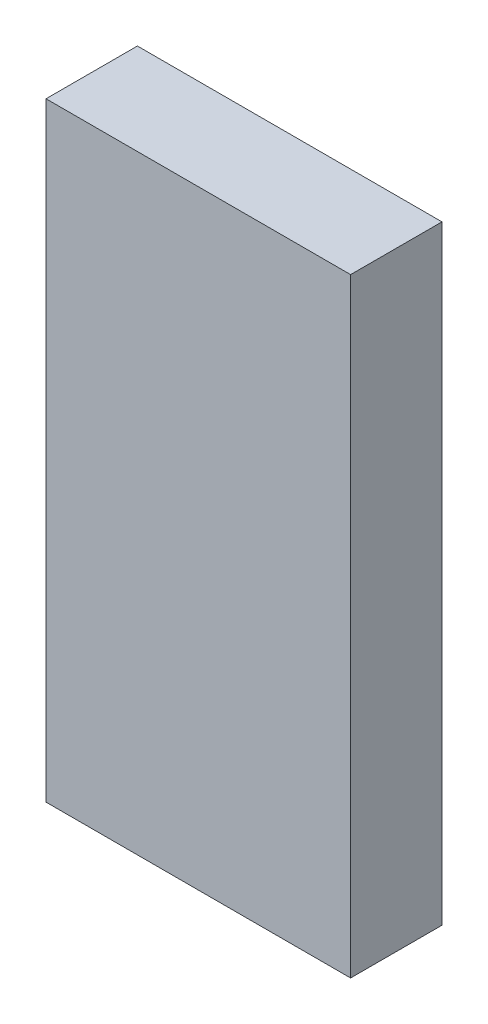
SolidWorks part; units mm, degrees
ref_plane "Front Plane" through (0, 0, 0) normal (0, 0, 1) x (1, 0, 0)
ref_plane "Top Plane" through (0, 0, 0) normal (0, 1, 0) x (1, 0, 0)
ref_plane "Right Plane" through (0, 0, 0) normal (1, 0, 0) x (0, 0, -1)
sketch "Sketch1" plane through (0, 0, 0) normal (0, 1, 0) x (1, 0, 0)
  line L1 (5, -1.5) -> (-5, -1.5)
  line L2 (5, -1.5) -> (5, 1.5)
  line L3 (5, 1.5) -> (-5, 1.5)
  line L4 (-5, -1.5) -> (-5, 1.5)
  line L5 (5, -1.5) -> (-5, 1.5) construction
  line L6 (5, 1.5) -> (-5, -1.5) construction
  point P0 (0, 0)
  dimension "D1" = 3
  dimension "D2" = 10
extrude "Boss-Extrude1" add sketch "Sketch1" along normal blind 20
